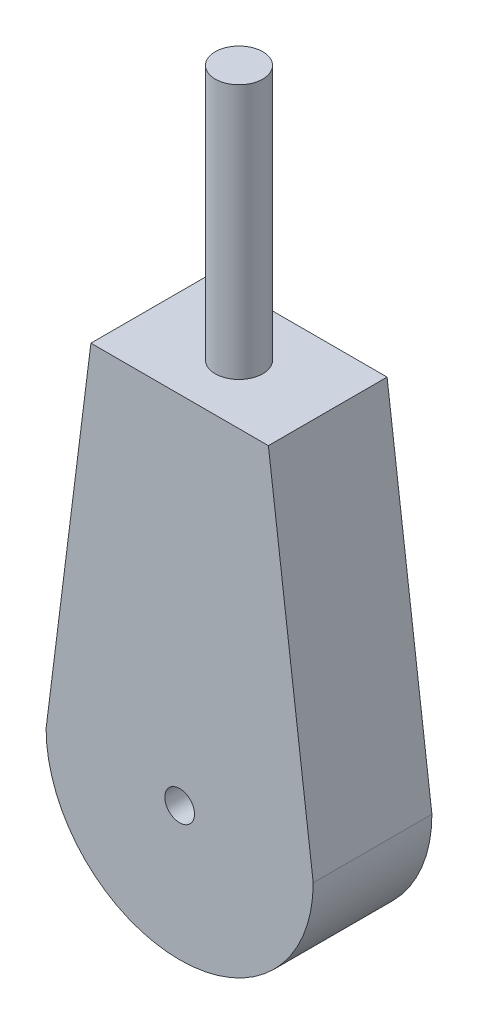
SolidWorks part; units mm, degrees
ref_plane "Ön Düzlem" through (0, 0, 0) normal (0, 0, 1) x (1, 0, 0)
ref_plane "Üst Düzlem" through (0, 0, 0) normal (0, 1, 0) x (1, 0, 0)
ref_plane "Sağ Düzlem" through (0, 0, 0) normal (1, 0, 0) x (0, 0, -1)
sketch "Sketch1" plane through (0, 0, 0) normal (0, 0, 1) x (1, 0, 0)
  line L1 (0, -22.5) -> (0, 60) construction
  line L4 (-22.5, 0) -> (-14.95, 60)
  line L5 (-14.95, 60) -> (14.95, 60)
  line L7 (22.5, 0) -> (14.95, 60)
  arc A0 (-22.5, 0) -> (22.5, 0) centre (0, 0) ccw
  dimension "D1" = 22.5
  dimension "D2" = 82.5
  dimension "D4" = 60
  dimension "D5" = 7.55
extrude "Boss-Extrude1" add sketch "Sketch1" along normal mid plane 20
sketch "Sketch3" plane through (0, 60, 0) normal (0, 1, 0) x (1, 0, 0)
  circle A0 centre (0, 0) radius 4
  dimension "D1" = 8
extrude "Boss-Extrude2" add sketch "Sketch3" along normal blind 43 contours A0
sketch "Sketch4" plane through (0, 0, 10) normal (0, 0, 1) x (1, 0, 0)
  circle A0 centre (0, 0) radius 2.5
  dimension "D1" = 5
extrude "Cut-Extrude1" cut sketch "Sketch4" against normal blind 5
sketch "Sketch6" plane through (0, 0, -10) normal (0, 0, -1) x (-1, 0, 0)
  circle A0 centre (0, 0) radius 12.5
  dimension "D1" = 25
extrude "Boss-Extrude3" add sketch "Sketch6" along normal blind 5
sketch "Sketch7" plane through (0, 0, -15) normal (0, 0, -1) x (-1, 0, 0)
  circle A0 centre (0, 0) radius 2.5
  dimension "D1" = 5
extrude "Cut-Extrude2" cut sketch "Sketch7" against normal blind 5
